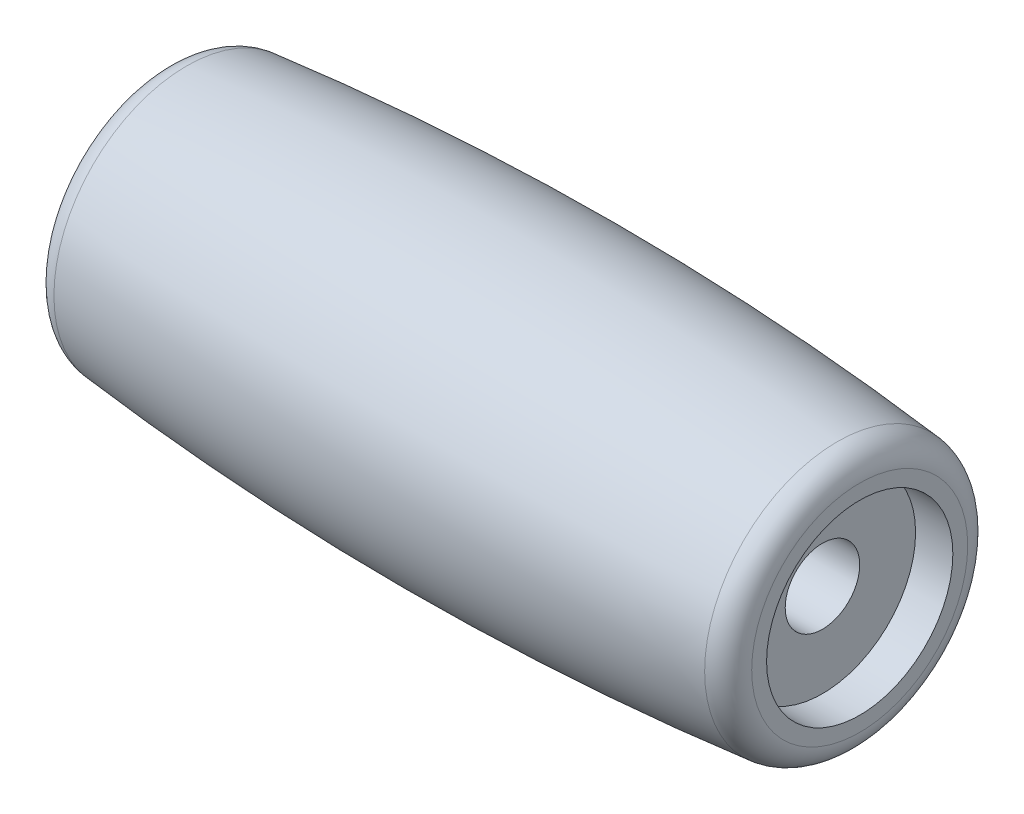
SolidWorks part; units mm, degrees
ref_plane "Front Plane" through (0, 0, 0) normal (0, 0, 1) x (1, 0, 0)
ref_plane "Top Plane" through (0, 0, 0) normal (0, 1, 0) x (1, 0, 0)
ref_plane "Right Plane" through (0, 0, 0) normal (1, 0, 0) x (0, 0, -1)
sketch "Sketch1" plane through (0, 0, 0) normal (0, 0, 1) x (1, 0, 0)
  line L0 (0, 6) -> (0, 0) construction
  line L1 (0, 0) -> (11.107, 0) construction
  line L2 (-12.5, 1.5) -> (12.5, 1.5)
  line L3 (12.5, 1.5) -> (12.5, 3.75)
  line L4 (12.5, 3.75) -> (14, 3.75)
  line L5 (14, 3.75) -> (14, 4.3486)
  line L6 (-14, 3.75) -> (-14, 4.3486)
  line L7 (-12.5, 3.75) -> (-14, 3.75)
  line L8 (-12.5, 1.5) -> (-12.5, 3.75)
  arc A0 (-13.1, 5.3436) -> (13.1, 5.3436) centre (0, -125.0417) cw
  arc A1 (14, 4.3486) -> (13.1, 5.3436) centre (13, 4.3486) ccw
  arc A2 (-14, 4.3486) -> (-13.1, 5.3436) centre (-13, 4.3486) cw
  point P10 (0, 1.5)
  point P16 (14, 5.25)
  point P19 (-14, 5.25)
  dimension "D7" = 1
  dimension "D1" = 1.5
  dimension "D2" = 3.75
  dimension "D3" = 1.5
  dimension "D4" = 1.5
  dimension "D5" = 14
  dimension "D6" = 6
revolve "Revolve1" add sketch "Sketch1" angle 360 about L1
